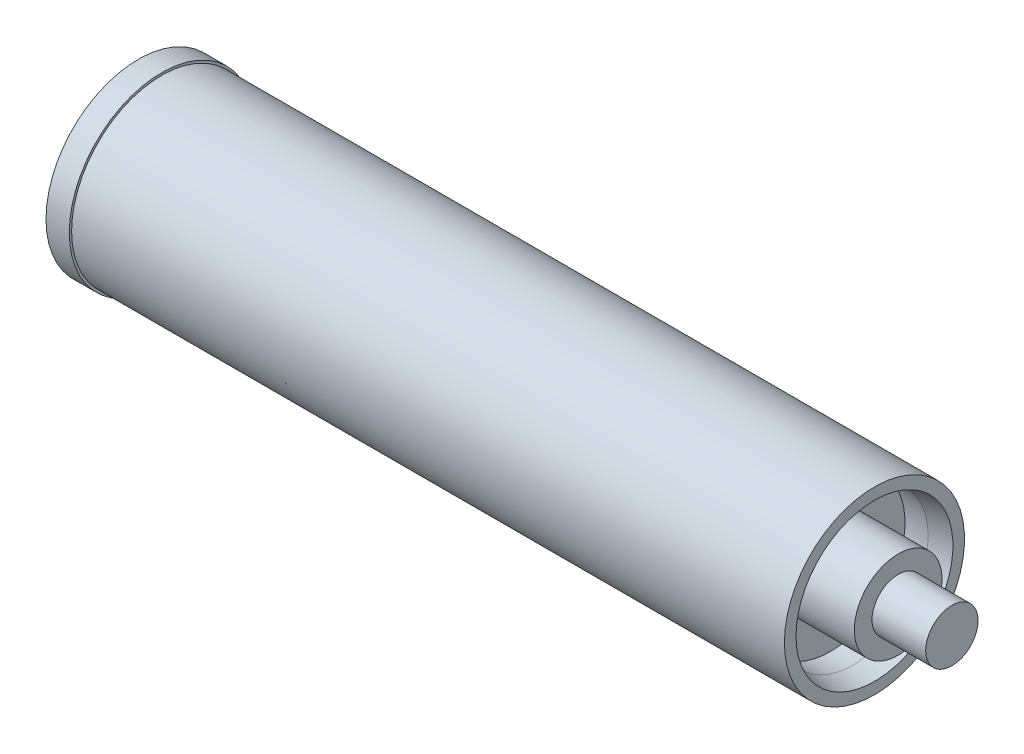
SolidWorks part; units mm, degrees
ref_plane "Plan de face" through (0, 0, 0) normal (0, 0, 1) x (1, 0, 0)
ref_plane "Plan de dessus" through (0, 0, 0) normal (0, 1, 0) x (1, 0, 0)
ref_plane "Plan de droite" through (0, 0, 0) normal (1, 0, 0) x (0, 0, -1)
sketch "Esquisse2" plane through (0, 0, 0) normal (0, 0, 1) x (1, 0, 0)
  line L0 (0, 0) -> (97.8436, 0) construction
  line L1 (0, -26) -> (0, 26) construction
  line L2 (0, 26) -> (12.7, 26)
  line L3 (12.7, 26) -> (12.7, 50.419) construction
  line L4 (12.7, 50.419) -> (25.4, 50.419)
  line L5 (25.4, 50.419) -> (25.4, 49.149)
  line L6 (25.4, 49.149) -> (414.3502, 49.149)
  line L7 (414.3502, 49.149) -> (414.3502, 42.8202)
  line L8 (414.3502, 42.8202) -> (403.0273, 40.5731)
  line L9 (403.0273, 40.5731) -> (390.4548, 40.5731)
  line L10 (390.4548, 40.5731) -> (390.4548, 23.9395)
  line L11 (390.4548, 23.9395) -> (427.3042, 23.9395)
  line L12 (427.3042, 23.9395) -> (427.3042, 14.2875)
  line L13 (427.3042, 14.2875) -> (456.5904, 14.2875)
  line L14 (456.5904, 14.2875) -> (456.5904, -14.2875) construction
  line L15 (456.5904, 0) -> (0, 0) construction
  line L16 (427.3042, -14.2875) -> (456.5904, -14.2875) construction
  line L17 (427.3042, -23.9395) -> (427.3042, -14.2875) construction
  line L18 (390.4548, -23.9395) -> (427.3042, -23.9395) construction
  line L19 (390.4548, -40.5731) -> (390.4548, -23.9395) construction
  line L20 (403.0273, -40.5731) -> (390.4548, -40.5731) construction
  line L21 (414.3502, -42.8202) -> (403.0273, -40.5731) construction
  line L22 (414.3502, -49.149) -> (414.3502, -42.8202) construction
  line L23 (25.4, -49.149) -> (414.3502, -49.149) construction
  line L24 (25.4, -50.419) -> (25.4, -49.149) construction
  line L25 (12.7, -50.419) -> (25.4, -50.419) construction
  line L26 (12.7, -26) -> (12.7, -50.419) construction
  line L27 (0, -26) -> (12.7, -26) construction
  line L28 (12.7, 50.419) -> (12.7, 38.2095)
  line L29 (12.7, 38.2095) -> (25.4, 35.6891)
  line L30 (25.4, 35.6891) -> (36.5674, 35.6891)
  line L31 (36.5674, 35.6891) -> (36.5674, 26)
  line L32 (36.5674, 26) -> (12.7, 26)
  line L33 (25.4, 35.6891) -> (25.4, 49.149) construction
  line L34 (36.5674, -26) -> (12.7, -26) construction
  line L35 (36.5674, -35.6891) -> (36.5674, -26) construction
  line L36 (25.4, -35.6891) -> (36.5674, -35.6891) construction
  line L37 (12.7, -38.2095) -> (25.4, -35.6891) construction
  line L38 (12.7, -50.419) -> (12.7, -38.2095) construction
  line L39 (0, 26) -> (0, 0)
  line L40 (0, 0) -> (456.5904, 0)
  line L41 (456.5904, 0) -> (456.5904, 14.2875)
  dimension "D1" = 443.8904
  dimension "D2" = 414.6042
  dimension "D3" = 401.6502
  dimension "D4" = 28.575
  dimension "D5" = 47.879
  dimension "D6" = 98.298
  dimension "D7" = 12.7
  dimension "D8" = 100.838
  dimension "D9" = 12.7
  dimension "D10" = 52
revolve "Révolution7" add sketch "Esquisse2" angle 360 about L0
sketch "Esquisse3" plane through (0, 0, 0) normal (0, 0, 1) x (1, 0, 0)
  line L0 (0, 0) -> (456.5904, 0) construction
  line L1 (456.5904, -14.2875) -> (456.5904, 14.2875) construction
  line L2 (0, 20) -> (0, 0)
  line L3 (0, 26) -> (0, -26) construction
  line L4 (0, 0) -> (390.0908, 0)
  line L5 (390.0908, 0) -> (390.4548, 12.9578)
  line L6 (390.4548, -40.5731) -> (390.4548, 40.5731) construction
  line L7 (390.4548, 12.9578) -> (381.0611, 12.9578)
  line L8 (381.0611, 12.9578) -> (381.0611, 44.271)
  line L9 (381.0611, 44.271) -> (65.8719, 44.271)
  line L10 (65.8719, 44.271) -> (34.083, 14.3276)
  line L11 (34.083, 14.3276) -> (19.083, 14.3276)
  line L12 (19.083, 14.3276) -> (0, 20)
  line L13 (36.5674, 26) -> (0, 26) construction
  dimension "D1" = 15
  dimension "D2" = 6
revolve "Enlèvement de matière-Révolution1" cut sketch "Esquisse3" angle 360 about L0
